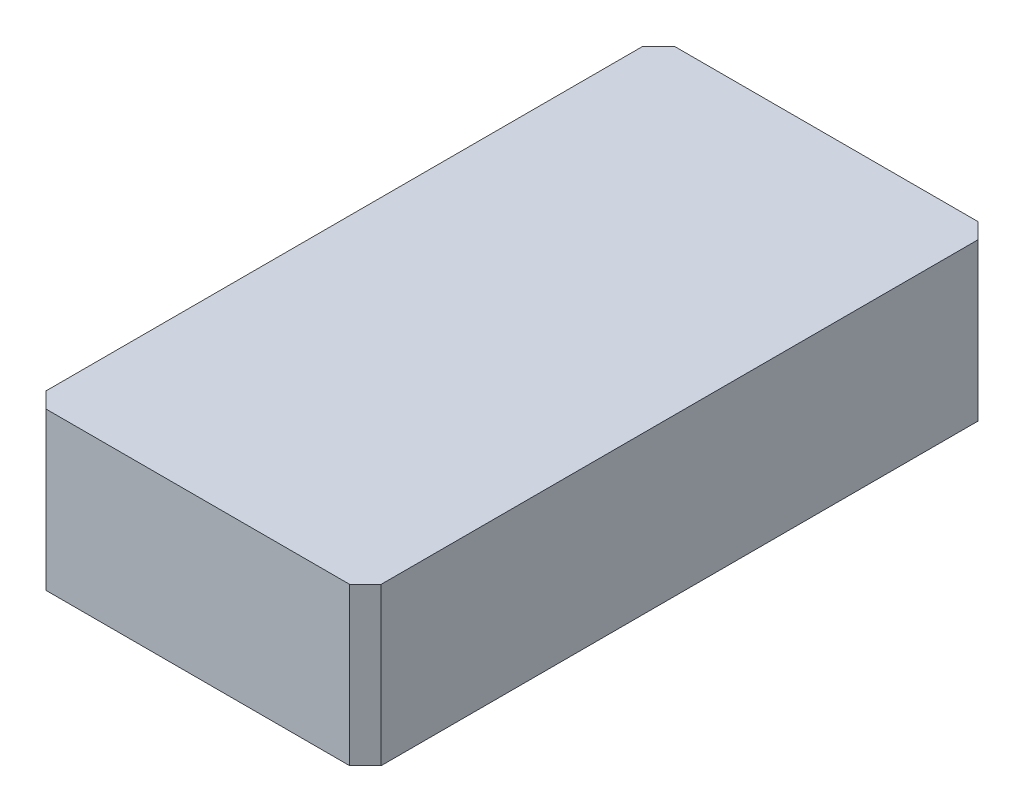
SolidWorks part; units mm, degrees
ref_plane "前视基准面" through (0, 0, 0) normal (0, 0, 1) x (1, 0, 0)
ref_plane "上视基准面" through (0, 0, 0) normal (0, 1, 0) x (1, 0, 0)
ref_plane "右视基准面" through (0, 0, 0) normal (1, 0, 0) x (0, 0, -1)
other "Configuration Table"
sketch "草图1" plane through (0, 0, 0) normal (0, 1, 0) x (1, 0, 0)
  line L0 (-14.5, -30) -> (14.5, -30)
  line L1 (14.5, -30) -> (16, -28.5)
  line L2 (16, -28.5) -> (16, 28.5)
  line L3 (16, 28.5) -> (14.5, 30)
  line L4 (14.5, 30) -> (-14.5, 30)
  line L5 (-14.5, 30) -> (-16, 28.5)
  line L6 (-16, 28.5) -> (-16, -28.5)
  line L7 (-16, -28.5) -> (-14.5, -30)
extrude "凸台-拉伸1" add sketch "草图1" along normal blind 15
